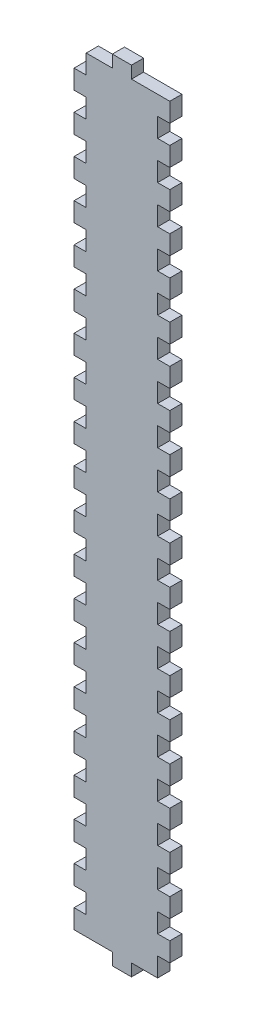
SolidWorks part; units mm, degrees
ref_plane "Front Plane" through (0, 0, 0) normal (0, 0, 1) x (1, 0, 0)
ref_plane "Top Plane" through (0, 0, 0) normal (0, 1, 0) x (1, 0, 0)
ref_plane "Right Plane" through (0, 0, 0) normal (1, 0, 0) x (0, 0, -1)
sketch "Sketch1" plane through (0, 0, 0) normal (0, 0, 1) x (1, 0, 0)
  line L1 (-18.65, -200) -> (18.65, -200)
  line L2 (-18.65, -200) -> (-18.65, 200)
  line L3 (-18.65, 200) -> (18.65, 200)
  line L4 (18.65, -200) -> (18.65, 200)
  line L5 (-18.65, -200) -> (18.65, 200) construction
  line L6 (-18.65, 200) -> (18.65, -200) construction
  point P0 (0, 0)
  dimension "D1" = 37.3
  dimension "D2" = 400
extrude "Boss-Extrude1" add sketch "Sketch1" along normal blind 6.35
sketch "Sketch10" plane through (0, 0, 0) normal (0, 0, 1) x (1, 0, 0)
  line L0 (-18.65, 200) -> (-18.65, -200) construction
  line L1 (-18.65, -190) -> (-25, -190)
  line L2 (-18.65, -190) -> (-18.65, -200)
  line L3 (-18.65, -200) -> (-25, -200)
  line L4 (-25, -190) -> (-25, -200)
  line L5 (-18.65, -200) -> (18.65, -200) construction
  dimension "D1" = 10
  dimension "D2" = 6.35
extrude "Boss-Extrude3" add sketch "Sketch10" along normal blind 6.35
sketch "Sketch11" plane through (0, 0, 0) normal (0, 0, 1) x (1, 0, 0)
  line L0 (18.65, -200) -> (18.65, 200) construction
  line L1 (18.65, -180) -> (25, -180)
  line L2 (18.65, -180) -> (18.65, -190)
  line L3 (18.65, -190) -> (25, -190)
  line L4 (25, -180) -> (25, -190)
  line L5 (-18.65, -190) -> (-25, -190) construction
  dimension "D1" = 6.35
  dimension "D2" = 10
extrude "Boss-Extrude4" add sketch "Sketch11" along normal blind 6.35
pattern_linear "LPattern5" count 20 spacing 20 along (0, 1, 0) of "Boss-Extrude3", "Boss-Extrude4"
sketch "Sketch2" plane through (0, 0, 0) normal (0, 0, 1) x (1, 0, 0)
  line L0 (-18.65, 200) -> (-18.65, 190) construction
  line L1 (-18.65, -180) -> (-25, -180)
  line L2 (-18.65, -180) -> (-18.65, -190)
  line L3 (-18.65, -190) -> (-25, -190)
  line L4 (-25, -180) -> (-25, -190)
  line L5 (-25, -200) -> (18.65, -200) construction
  line L6 (3.175, 200) -> (3.175, -101.8887) construction
  line L7 (25, 200) -> (-18.65, 200) construction
  line L8 (31.35, -180) -> (31.35, -190)
  line L9 (25, -190) -> (31.35, -190)
  line L10 (25, -180) -> (25, -190)
  line L11 (25, -180) -> (31.35, -180)
  point P8 (-18.65, -185)
  dimension "D1" = 10
  dimension "D2" = 6.35
  dimension "D3" = 10
extrude "Boss-Extrude2" [suppressed] add sketch "Sketch2" along normal blind 6.35
pattern_linear "LPattern1" [suppressed] count 20 spacing 20
hole_wizard "dogBone01" [suppressed] positions "Sketch3" profile "Sketch4" hole size "1/16" standard "ANSI Inch"
sketch "Sketch3" [suppressed] plane through (0, 0, 6.35) normal (0, 0, 1) x (1, 0, 0)
  line L0 (18.65, -190) -> (19.7725, -190) construction
  line L1 (18.65, -190) -> (18.65, -191.1225) construction
  line L2 (18.65, -190) -> (25, -190) construction
  line L3 (0, 200) -> (0, -200) construction
  line L4 (25, 200) -> (-25, 200) construction
  line L5 (-18.65, -200) -> (18.65, -200) construction
  circle A0 centre (19.2113, -190.5613) radius 0.7937
  point P8 (19.2113, -190.5613)
  point P31 (-19.2113, -190.5613)
  dimension "D1" = 1.5875
sketch "Sketch4" plane through (19.2113, -190.5613, 6.35) normal (1, 0, 0) x (0, -1, 0)
  line L0 (0, 0) -> (0, 6.35)
  line L1 (0, 6.35) -> (0.7937, 6.35)
  line L2 (0.7937, 6.35) -> (0.7937, 0)
  line L5 (0.7937, 0) -> (0, 0)
  line L11 (0, -6.35) -> (0, 107.95) construction
  dimension "Thru Hole Dia." = 1.5875
  dimension "Thru Hole Depth" = 6.35
hole_wizard "dogBone02" [suppressed] positions "Sketch8" profile "Sketch9" hole size "1/16" standard "ANSI Inch"
sketch "Sketch8" [suppressed] plane through (0, 0, 6.35) normal (0, 0, 1) x (1, 0, 0)
  line L0 (18.65, -180) -> (18.65, -178.8775) construction
  line L1 (18.65, -180) -> (18.65, -170) construction
  line L2 (18.65, -180) -> (19.7725, -180) construction
  line L3 (25, -180) -> (18.65, -180) construction
  line L4 (0, 200) -> (0, -200) construction
  line L5 (25, 200) -> (-25, 200) construction
  line L6 (-18.65, -200) -> (18.65, -200) construction
  circle A0 centre (19.2113, -179.4387) radius 0.7937
  point P1 (19.2113, -179.4387)
  point P23 (-19.2113, -179.4387)
  dimension "D1" = 1.5875
sketch "Sketch9" plane through (19.2113, -179.4387, 6.35) normal (1, 0, 0) x (0, -1, 0)
  line L0 (0, 0) -> (0, 6.35)
  line L1 (0, 6.35) -> (0.7937, 6.35)
  line L2 (0.7937, 6.35) -> (0.7937, 0)
  line L5 (0.7937, 0) -> (0, 0)
  line L11 (0, -6.35) -> (0, 107.95) construction
  dimension "Thru Hole Dia." = 1.5875
  dimension "Thru Hole Depth" = 6.35
pattern_linear "LPattern2" [suppressed] count 10 spacing 20
pattern_linear "LPattern4" [suppressed] count 19 spacing 20
sketch "Sketch12" plane through (0, 0, 0) normal (0, 0, 1) x (1, 0, 0)
  line L0 (0, 200) -> (0, -200) construction
  line L1 (25, 200) -> (-18.65, 200) construction
  line L2 (-25, -200) -> (18.65, -200) construction
  line L4 (-5, 200) -> (5, 200)
  line L5 (-5, 200) -> (-5, 206.35)
  line L6 (-5, 206.35) -> (5, 206.35)
  line L7 (5, 200) -> (5, 206.35)
  point P11 (0, 200)
  point P16 (0, 0)
  dimension "D1" = 10
  dimension "D2" = 6.35
extrude "Boss-Extrude5" add sketch "Sketch12" along normal blind 6.35
mirror "Mirror1" about plane through (0, 0, 0) normal (0, 1, 0) of "Boss-Extrude5"
equation "\"z\"= 40cm"
equation "\"D2@Sketch1\"=\"z\""
equation "\"tWidth\"= 1cm"
equation "\"tHeight\"=0.635"
equation "\"D2@Sketch10\"=\"tHeight\""
equation "\"D1@Boss-Extrude3\"=\"tHeight\""
equation "\"D1@Sketch10\"=\"tWidth\""
equation "\"D1@Sketch11\"=\"tHeight\""
equation "\"D2@Sketch11\"=\"tWidth\""
equation "\"D1@Boss-Extrude4\"=\"tHeight\""
equation "\"D2@Sketch2\"=\"tHeight\""
equation "\"D3@Sketch2\"=\"tWidth\""
equation "\"D1@Sketch2\"=\"tWidth\""
equation "\"D1@Sketch12\"=\"tWidth\""
equation "\"D1@Boss-Extrude5\"=\"tHeight\""
